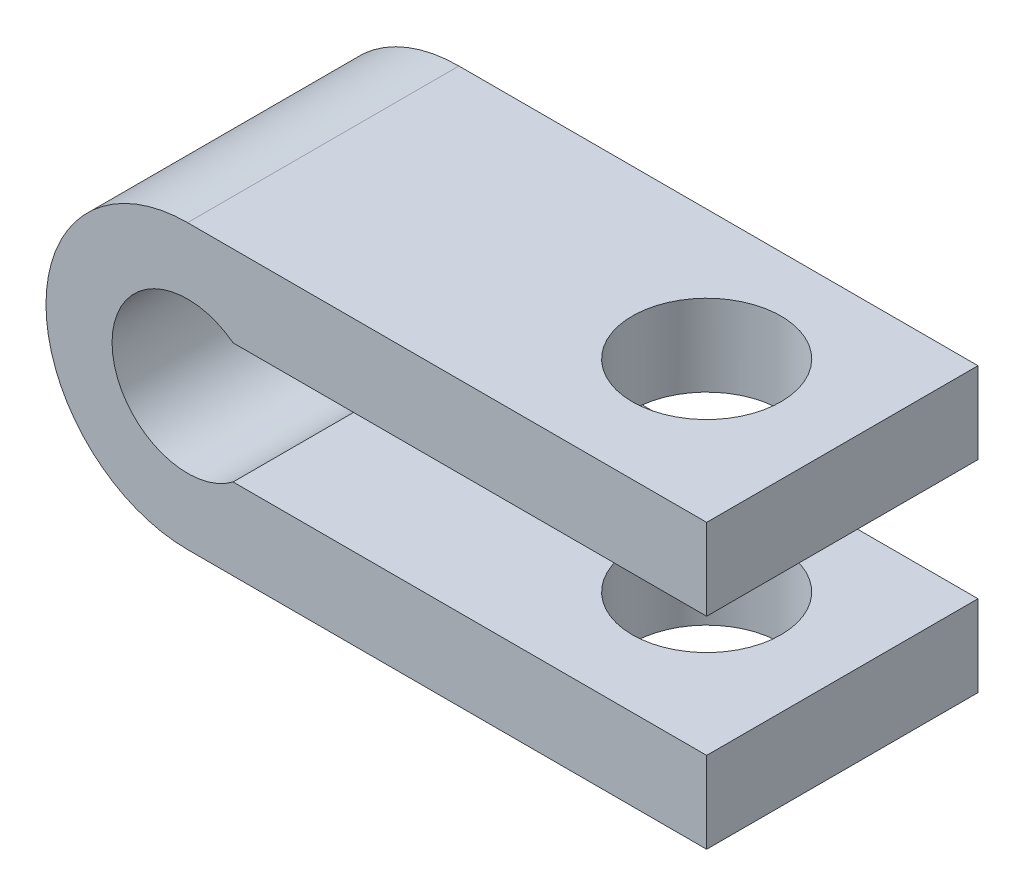
SolidWorks part; units mm, degrees
material "ABS"
ref_plane "Front Plane" through (0, 0, 0) normal (0, 0, 1) x (1, 0, 0)
ref_plane "Top Plane" through (0, 0, 0) normal (0, 1, 0) x (1, 0, 0)
ref_plane "Right Plane" through (0, 0, 0) normal (1, 0, 0) x (0, 0, -1)
sketch "Sketch1" plane through (0, 0, 0) normal (0, 0, 1) x (1, 0, 0)
  line L0 (0, 6) -> (22, 6)
  line L1 (22, 6) -> (22, 2.5527)
  line L2 (22, 2.5527) -> (1.9297, 2.5527)
  line L3 (-11.5353, 0) -> (18.1518, 0) construction
  line L4 (22, -2.5527) -> (1.9297, -2.5527)
  line L5 (22, -6) -> (22, -2.5527)
  line L6 (0, -6) -> (22, -6)
  arc A0 (1.9297, 2.5527) -> (1.9297, -2.5527) centre (0, 0) ccw
  arc A2 (0, 6) -> (0, -6) centre (0, 0) ccw
  dimension "D1" = 3.2
  dimension "D2" = 6
  dimension "D3" = 22
  dimension "D4" = 5.1054
extrude "Boss-Extrude1" add sketch "Sketch1" along normal blind 12
sketch "Sketch2" plane through (0, 0, 0) normal (0, 1, 0) x (1, 0, 0)
  circle A0 centre (16, -6) radius 3.15
  dimension "D3" = 6.3
  dimension "D1" = 16
  dimension "D2" = 6
extrude "Cut-Extrude1" cut sketch "Sketch2" against normal through all and the other way through all
chamfer "Chamfer1" distance 0.5 angle 45 8 edges at (11.9648, 2.5527, 0) (11.9648, -2.5527, 0) (-3.2, 0, 0) (22, -4.2764, 0) (11, -6, 0) (-6, 0, 0) (11, 6, 0) (22, 4.2764, 0)
